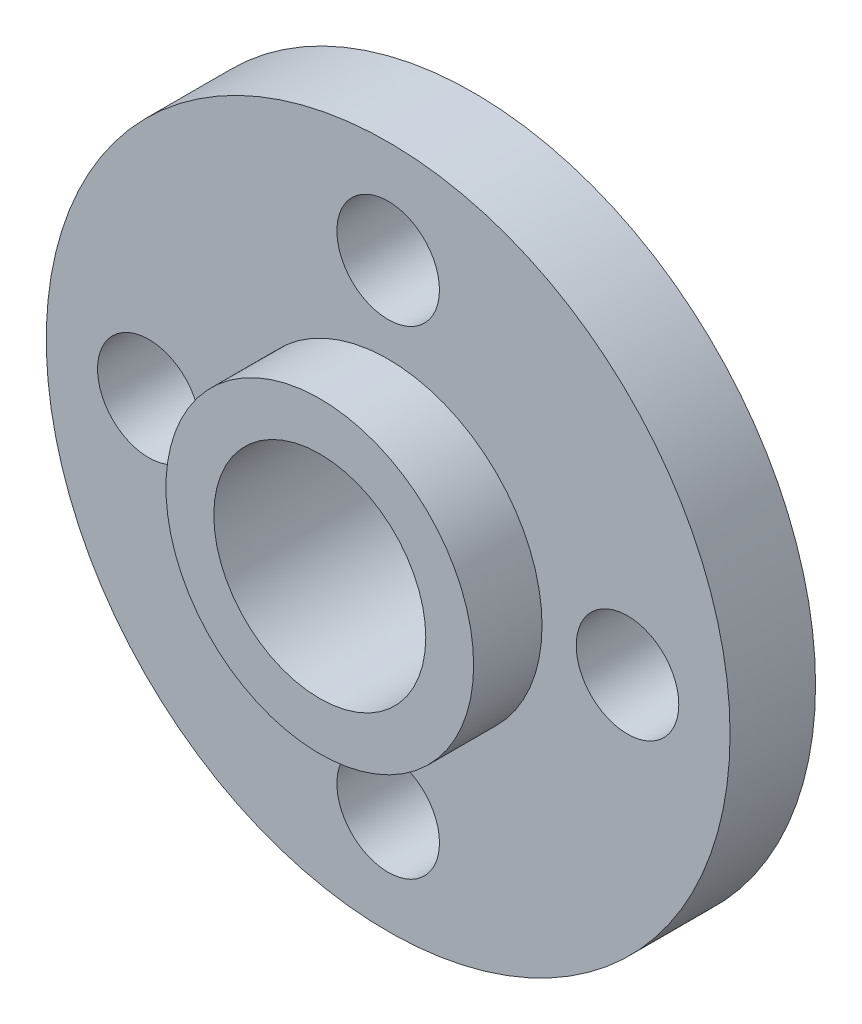
SolidWorks part; units mm, degrees
ref_plane "前视基准面" through (0, 0, 0) normal (0, 0, 1) x (1, 0, 0)
ref_plane "上视基准面" through (0, 0, 0) normal (0, 1, 0) x (1, 0, 0)
ref_plane "右视基准面" through (0, 0, 0) normal (1, 0, 0) x (0, 0, -1)
other "Configuration Table"
sketch "草图1" plane through (0, 0, 0) normal (0, 0, 1) x (1, 0, 0)
  circle A0 centre (0, 0) radius 10
  circle A1 centre (0, 0) radius 7 construction
  circle A2 centre (0, 7) radius 1.5
  circle A3 centre (7, 0) radius 1.5
  circle A4 centre (0, -7) radius 1.5
  circle A5 centre (-7, 0) radius 1.5
  circle A6 centre (0, 0) radius 3.1
  point P9 (0, 0)
  point P12 (0, 0)
  point P17 (0, 0)
  dimension "D1" = 20
  dimension "D2" = 14
  dimension "D3" = 3
  dimension "D5" = 6.2
  dimension "D4" = 4
extrude "凸台-拉伸1" add sketch "草图1" along normal blind 2.5
sketch "草图2" plane through (0, 0, 2.5) normal (0, 0, 1) x (1, 0, 0)
  circle A0 centre (0, 0) radius 3.1 construction
  circle A1 centre (0, 0) radius 3.1
  circle A2 centre (0, 0) radius 4.5
  dimension "D1" = 1.4
extrude "凸台-拉伸2" add sketch "草图2" along normal blind 2
